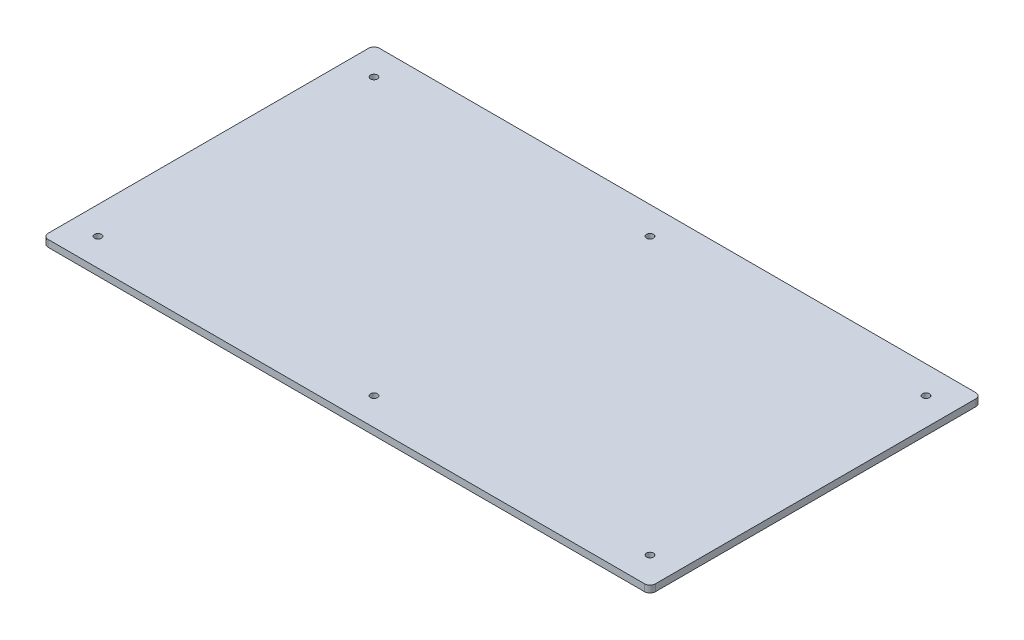
SolidWorks part; units mm, degrees
ref_plane "Front Plane" through (0, 0, 0) normal (0, 0, 1) x (1, 0, 0)
ref_plane "Top Plane" through (0, 0, 0) normal (0, 1, 0) x (1, 0, 0)
ref_plane "Right Plane" through (0, 0, 0) normal (1, 0, 0) x (0, 0, -1)
sketch "Sketch1" plane through (0, 0, 0) normal (0, 1, 0) x (1, 0, 0)
  line L1 (1048.9967, -228.9519) -> (-68.6033, -228.9519)
  line L2 (1048.9967, -228.9519) -> (1048.9967, 380.6481)
  line L3 (1048.9967, 380.6481) -> (-68.6033, 380.6481)
  line L4 (-68.6033, -228.9519) -> (-68.6033, 380.6481)
  dimension "D1" = 1117.6
  dimension "D2" = 609.6
extrude "Boss-Extrude1" add sketch "Sketch1" along normal blind 12.7
sketch "Sketch2" plane through (0, 12.7, 0) normal (0, 1, 0) x (1, 0, 0)
  line L0 (-68.6033, 380.6481) -> (-68.6033, -228.9519) construction
  line L1 (-68.6033, -228.9519) -> (1048.9967, -228.9519) construction
  line L2 (1048.9967, 380.6481) -> (-68.6033, 380.6481) construction
  line L3 (1048.9967, -228.9519) -> (1048.9967, 380.6481) construction
  circle A0 centre (998.1967, -178.1519) radius 6.35
  circle A1 centre (-17.8033, -178.1519) radius 6.35
  circle A2 centre (-17.8033, 329.8481) radius 6.35
  circle A3 centre (998.1967, 329.8481) radius 6.35
  dimension "D1" = 12.7
  dimension "D2" = 12.7
  dimension "D3" = 12.7
  dimension "D4" = 12.7
  dimension "D5" = 50.8
  dimension "D6" = 50.8
  dimension "D7" = 50.8
  dimension "D8" = 50.8
  dimension "D9" = 50.8
  dimension "D10" = 50.8
  dimension "D11" = 50.8
  dimension "D12" = 50.8
extrude "Cut-Extrude1" cut sketch "Sketch2" against normal through all
sketch "Sketch3" plane through (0, 12.7, 0) normal (0, 1, 0) x (1, 0, 0)
  line L0 (-68.6033, -228.9519) -> (1048.9967, -228.9519) construction
  line L1 (1048.9967, -228.9519) -> (1048.9967, 380.6481) construction
  line L2 (1048.9967, 380.6481) -> (-68.6033, 380.6481) construction
  circle A0 centre (490.1967, -178.1519) radius 6.35
  circle A1 centre (490.1967, 329.8481) radius 6.35
  dimension "D1" = 12.7
  dimension "D2" = 12.7
  dimension "D3" = 50.8
  dimension "D4" = 558.8
  dimension "D5" = 50.8
  dimension "D6" = 558.8
extrude "Cut-Extrude2" cut sketch "Sketch3" against normal through all
fillet "Fillet1" radius 10 4 edges at (-68.6033, 6.35, 228.9519) (-68.6033, 6.35, -380.6481) (1048.9967, 6.35, 228.9519) (1048.9967, 6.35, -380.6481)
